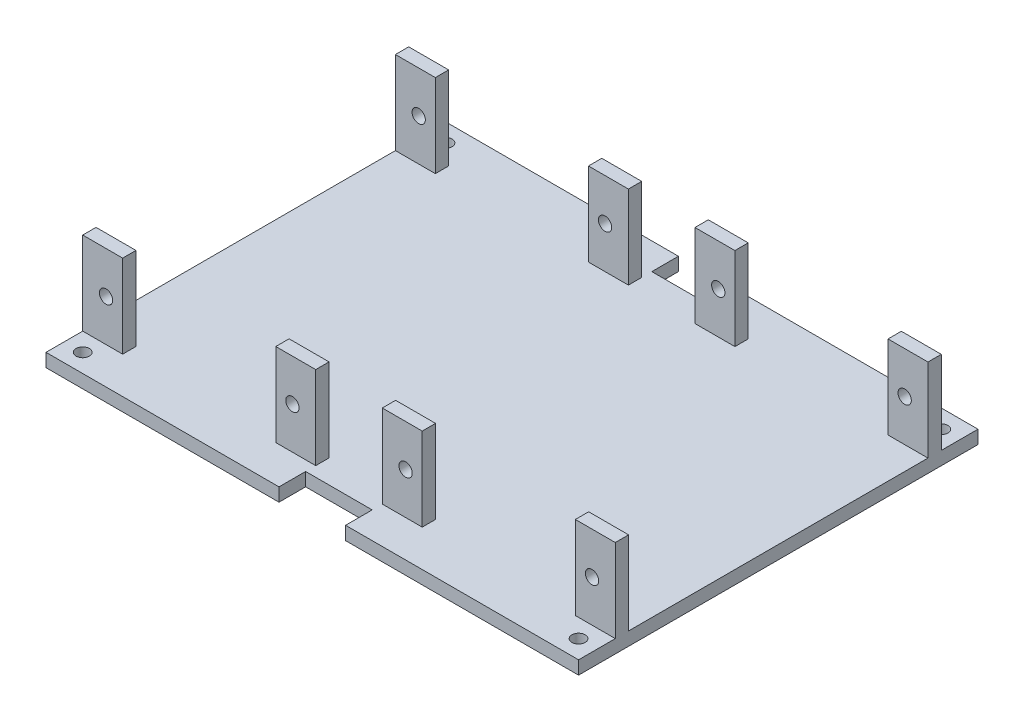
SolidWorks part; units mm, degrees
ref_plane "Front Plane" through (0, 0, 0) normal (0, 0, 1) x (1, 0, 0)
ref_plane "Top Plane" through (0, 0, 0) normal (0, 1, 0) x (1, 0, 0)
ref_plane "Right Plane" through (0, 0, 0) normal (1, 0, 0) x (0, 0, -1)
sketch "Sketch1" plane through (0, 0, 0) normal (0, 1, 0) x (1, 0, 0)
  line L1 (-31.9155, 7.3699) -> (48.0845, 7.3699)
  line L2 (-31.9155, 7.3699) -> (-31.9155, -52.6301)
  line L3 (-31.9155, -52.6301) -> (48.0845, -52.6301)
  line L4 (48.0845, 7.3699) -> (48.0845, -52.6301)
  dimension "D1" = 80
  dimension "D2" = 60
extrude "Boss-Extrude1" add sketch "Sketch1" along normal blind 2
sketch "Sketch2" plane through (0, 2, 0) normal (0, 1, 0) x (1, 0, 0)
  line L0 (-31.9155, 7.3699) -> (-31.9155, -52.6301) construction
  line L1 (-31.9155, -45.1143) -> (3.0845, -45.1143)
  line L2 (-31.9155, -45.1143) -> (-31.9155, -47.1143)
  line L3 (-31.9155, -47.1143) -> (3.0845, -47.1143)
  line L4 (3.0845, -45.1143) -> (3.0845, -47.1143)
  line L5 (-31.9155, -52.6301) -> (48.0845, -52.6301) construction
  dimension "D1" = 2
  dimension "D2" = 35
  dimension "D3" = 0
  dimension "D4" = 5.5158
extrude "Boss-Extrude2" add sketch "Sketch2" along normal blind 12.5
sketch "Sketch3" plane through (0, 0, 47.1143) normal (0, 0, 1) x (1, 0, 0)
  line L0 (-31.9155, 14.5) -> (3.0845, 14.5) construction
  line L1 (-25.9155, 14.5) -> (-2.9155, 14.5)
  line L2 (-25.9155, 14.5) -> (-25.9155, 2)
  line L3 (-25.9155, 2) -> (-2.9155, 2)
  line L4 (-2.9155, 14.5) -> (-2.9155, 2)
  circle A0 centre (-0.4155, 8.25) radius 1
  circle A1 centre (-28.4155, 8.25) radius 1
  point P4 (-14.4155, 14.5)
  point P7 (-14.4155, 14.5)
  point P12 (-2.9155, 8.25)
  point P14 (-25.9155, 8.25)
  dimension "D3" = 2
  dimension "D4" = 2
  dimension "D1" = 0
  dimension "D2" = 2.5
  dimension "D5" = 2.5
  dimension "D6" = 0
  dimension "D7" = 0
  dimension "D8" = 12.5
  dimension "D9" = 0
  dimension "D10" = 23
extrude "Cut-Extrude1" cut sketch "Sketch3" against normal up to next
ref_plane "Plane1" through (8.0845, 0, 0) normal (1, 0, 0) x (0, 0, -1)
ref_plane "Plane2" through (0, 0, 22.6301) normal (0, 0, 1) x (1, 0, 0)
mirror "Mirror1" about plane through (8.0845, 0, 0) normal (1, 0, 0) of "Cut-Extrude1", "Boss-Extrude2"
mirror "Mirror2" about plane through (0, 0, 22.6301) normal (0, 0, 1) of "Mirror1", "Boss-Extrude2", "Cut-Extrude1"
sketch "Sketch4" plane through (0, 2, 0) normal (0, 1, 0) x (1, 0, 0)
  line L0 (-31.9155, -47.1143) -> (-31.9155, -52.6301) construction
  circle A0 centre (-29.1555, -49.8722) radius 1
  point P4 (-31.9155, -49.8722)
  dimension "D1" = 2
  dimension "D2" = 0
  dimension "D3" = 2.76
extrude "Cut-Extrude2" cut sketch "Sketch4" against normal up to next
mirror "Mirror3" about plane through (8.0845, 0, 0) normal (1, 0, 0) of "Cut-Extrude2"
mirror "Mirror4" about plane through (0, 0, 22.6301) normal (0, 0, 1) of "Mirror3", "Cut-Extrude2"
sketch "Sketch5" plane through (0, 2, 0) normal (0, 1, 0) x (1, 0, 0)
  line L0 (48.0845, 7.3699) -> (-31.9155, 7.3699) construction
  line L1 (3.0845, 7.3699) -> (13.0845, 7.3699)
  line L2 (3.0845, 7.3699) -> (3.0845, 3.3699)
  line L3 (3.0845, 3.3699) -> (13.0845, 3.3699)
  line L4 (13.0845, 7.3699) -> (13.0845, 3.3699)
  line L5 (8.0845, -7.975) -> (8.0845, 7.975) construction
  point P6 (8.0845, 3.3699)
  dimension "D1" = 0
  dimension "D2" = 10
  dimension "D3" = 4
extrude "Cut-Extrude3" cut sketch "Sketch5" against normal blind 10
mirror "Mirror5" about plane through (0, 0, 22.6301) normal (0, 0, 1) of "Cut-Extrude3"
